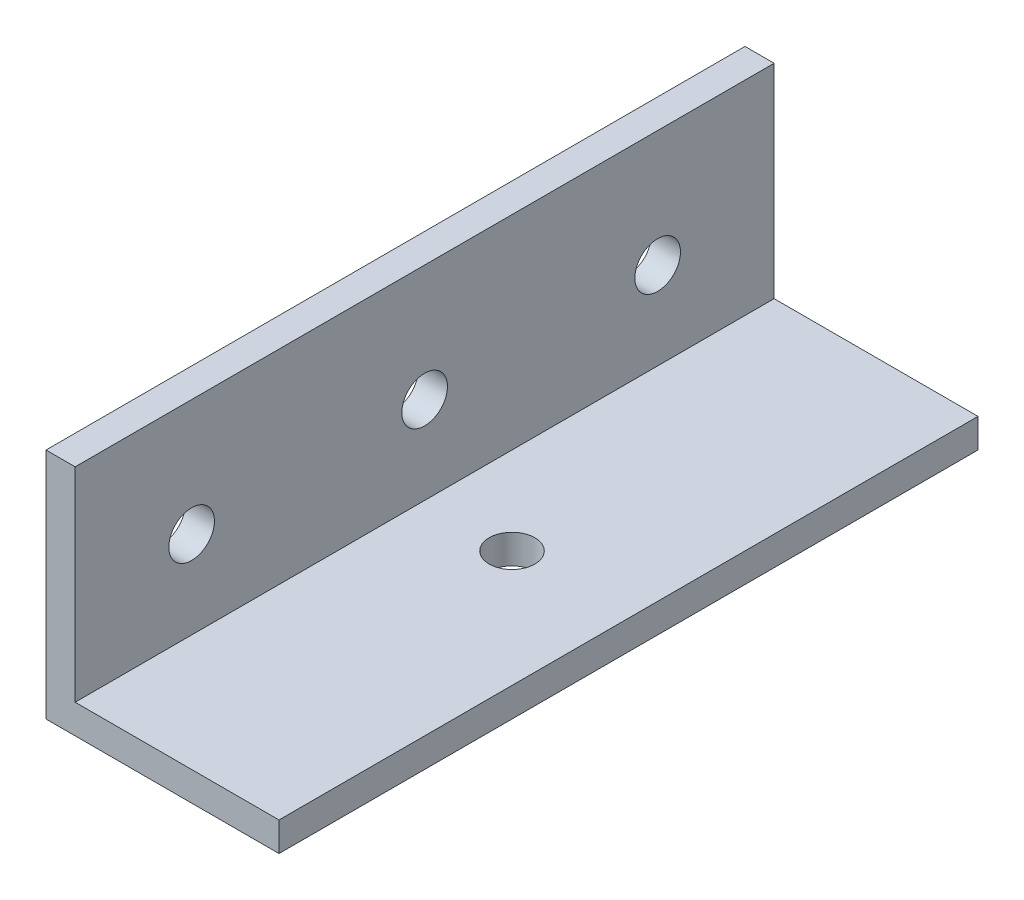
SolidWorks part; units mm, degrees
material "6061-T6 (SS)"
ref_plane "Front Plane" through (0, 0, 0) normal (0, 0, 1) x (1, 0, 0)
ref_plane "Top Plane" through (0, 0, 0) normal (0, 1, 0) x (1, 0, 0)
ref_plane "Right Plane" through (0, 0, 0) normal (1, 0, 0) x (0, 0, -1)
sketch "Sketch1" plane through (0, 0, 0) normal (0, 0, 1) x (1, 0, 0)
  line L0 (3.175, 25.4) -> (3.175, 3.175)
  line L1 (0, 0) -> (25.4, 0)
  line L2 (0, 0) -> (0, 25.4)
  line L3 (0, 25.4) -> (3.175, 25.4)
  line L4 (25.4, 0) -> (25.4, 3.175)
  line L5 (3.175, 3.175) -> (25.4, 3.175)
  dimension "D1" = 3.175
  dimension "D2" = 25.4
  dimension "D3" = 3.175
  dimension "D4" = 25.4
extrude "Boss-Extrude1" add sketch "Sketch1" along normal blind 76.2
sketch "Sketch7" plane through (3.175, 0, 0) normal (1, 0, 0) x (0, 0, -1)
  line L0 (-76.2, 25.4) -> (0, 25.4) construction
  line L1 (-76.2, 3.175) -> (-76.2, 25.4) construction
  circle A0 centre (-63.5, 12.7) radius 2.4892
  circle A1 centre (-38.1, 12.7) radius 2.4892
  circle A2 centre (-12.7, 12.7) radius 2.4892
  dimension "D1" = 12.7
  dimension "D3" = 4.9784
  dimension "D2" = 12.7
extrude "Cut-Extrude4" cut sketch "Sketch7" against normal through all
sketch "Sketch8" plane through (0, 3.175, 0) normal (0, 1, 0) x (1, 0, 0)
  line L0 (25.4, -76.2) -> (3.175, -76.2) construction
  line L1 (25.4, -76.2) -> (25.4, 0) construction
  circle A0 centre (12.7, -38.1) radius 2.4892
  dimension "D1" = 4.9784
  dimension "D2" = 38.1
  dimension "D3" = 12.7
extrude "Cut-Extrude5" cut sketch "Sketch8" against normal through all
